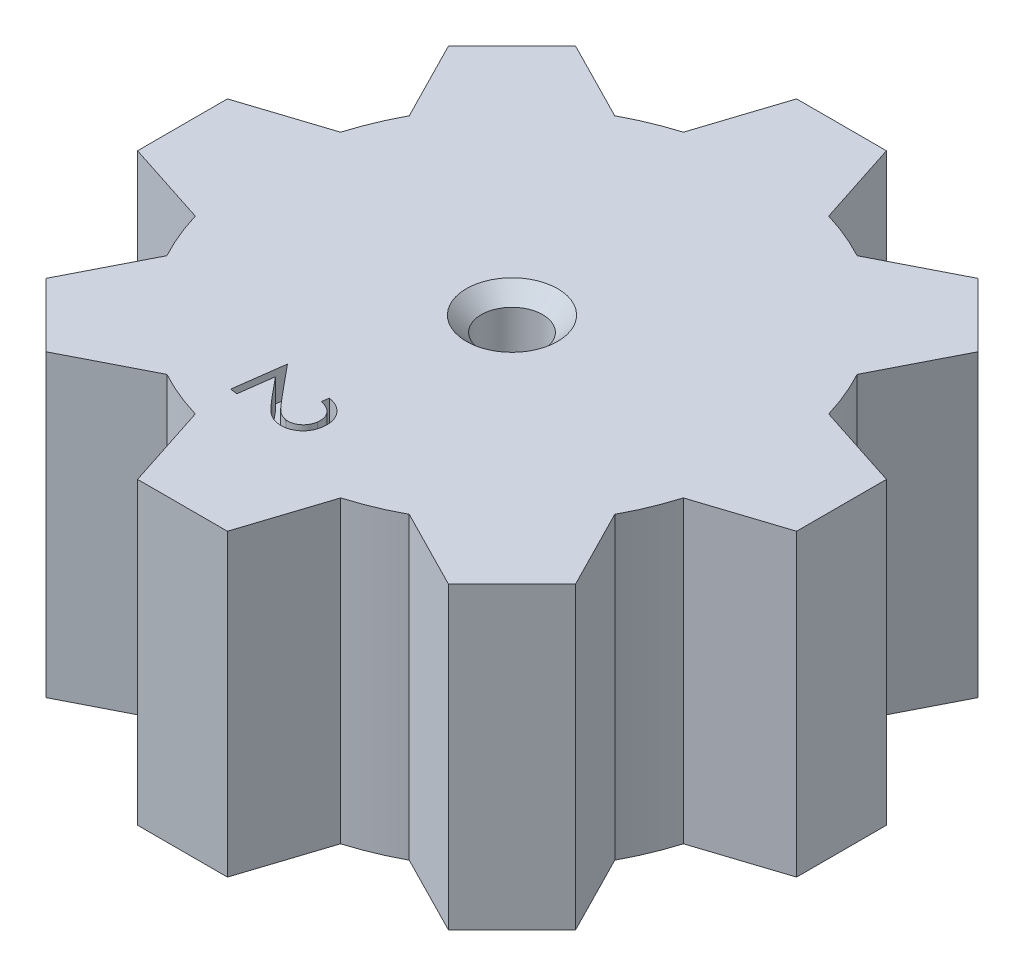
SolidWorks part; units mm, degrees
ref_plane "Front Plane" through (0, 0, 0) normal (0, 0, 1) x (1, 0, 0)
ref_plane "Top Plane" through (0, 0, 0) normal (0, 1, 0) x (1, 0, 0)
ref_plane "Right Plane" through (0, 0, 0) normal (1, 0, 0) x (0, 0, -1)
sketch "Sketch1" plane through (0, 0, 0) normal (0, 1, 0) x (1, 0, 0)
  line L1 (-0.25, 4.2426) -> (0.25, 4.2426) construction
  line L39 (0, 8.5) -> (0, 11) construction
  line L40 (-1.5, 11) -> (1.5, 11)
  line L41 (-1.5, 11) -> (-2.4259, 8.1465)
  line L42 (1.5, 11) -> (2.4259, 8.1465)
  line L43 (6.7175, 8.8388) -> (4.045, 7.4758)
  line L44 (6.7175, 8.8388) -> (8.8388, 6.7175)
  line L45 (8.8388, 6.7175) -> (7.4758, 4.045)
  line L46 (11, 1.5) -> (8.1465, 2.4259)
  line L47 (11, 1.5) -> (11, -1.5)
  line L48 (11, -1.5) -> (8.1465, -2.4259)
  line L49 (8.8388, -6.7175) -> (7.4758, -4.045)
  line L50 (8.8388, -6.7175) -> (6.7175, -8.8388)
  line L51 (6.7175, -8.8388) -> (4.045, -7.4758)
  line L52 (1.5, -11) -> (2.4259, -8.1465)
  line L53 (1.5, -11) -> (-1.5, -11)
  line L54 (-1.5, -11) -> (-2.4259, -8.1465)
  line L55 (-6.7175, -8.8388) -> (-4.045, -7.4758)
  line L56 (-6.7175, -8.8388) -> (-8.8388, -6.7175)
  line L57 (-8.8388, -6.7175) -> (-7.4758, -4.045)
  line L58 (-11, -1.5) -> (-8.1465, -2.4259)
  line L59 (-11, -1.5) -> (-11, 1.5)
  line L60 (-11, 1.5) -> (-8.1465, 2.4259)
  line L61 (-8.8388, 6.7175) -> (-7.4758, 4.045)
  line L62 (-8.8388, 6.7175) -> (-6.7175, 8.8388)
  line L63 (-6.7175, 8.8388) -> (-4.045, 7.4758)
  circle A0 centre (0, 0) radius 1.025
  circle A1 centre (0, 0) radius 5.25 construction
  circle A14 centre (0, 0) radius 8.5 construction
  arc A15 (2.4259, 8.1465) -> (4.045, 7.4758) centre (0, 0) cw
  arc A16 (7.4758, 4.045) -> (8.1465, 2.4259) centre (0, 0) cw
  arc A17 (8.1465, -2.4259) -> (7.4758, -4.045) centre (0, 0) cw
  arc A18 (4.045, -7.4758) -> (2.4259, -8.1465) centre (0, 0) cw
  arc A19 (-2.4259, -8.1465) -> (-4.045, -7.4758) centre (0, 0) cw
  arc A20 (-7.4758, -4.045) -> (-8.1465, -2.4259) centre (0, 0) cw
  arc A21 (-8.1465, 2.4259) -> (-7.4758, 4.045) centre (0, 0) cw
  arc A22 (-4.045, 7.4758) -> (-2.4259, 8.1465) centre (0, 0) cw
  point P31 (0, 0)
  point P60 (0, 0)
  point P71 (0, 11)
  point P105 (0, 0)
  dimension "D1" = 2.05
  dimension "D2" = 10.5
  dimension "D5" = 17
  dimension "D6" = 2.5
  dimension "D7" = 3
  dimension "D8" = 3
  dimension "D9" = 8
extrude "Boss-Extrude1" add sketch "Sketch1" along normal blind 10
sketch "Sketch2" plane through (0, 10, 0) normal (0, 1, 0) x (1, 0, 0)
  circle A0 centre (0, -6) radius 2.5 construction
  text T0 "2\r\n" font "Century Gothic" height 2.5
  dimension "D2" = 5
  dimension "D1" = 6
extrude "Cut-Extrude1" cut sketch "Sketch2" against normal blind 1
chamfer "Chamfer1" distance 0.5 angle 45 1 edges at (0, 10, 1.025)
